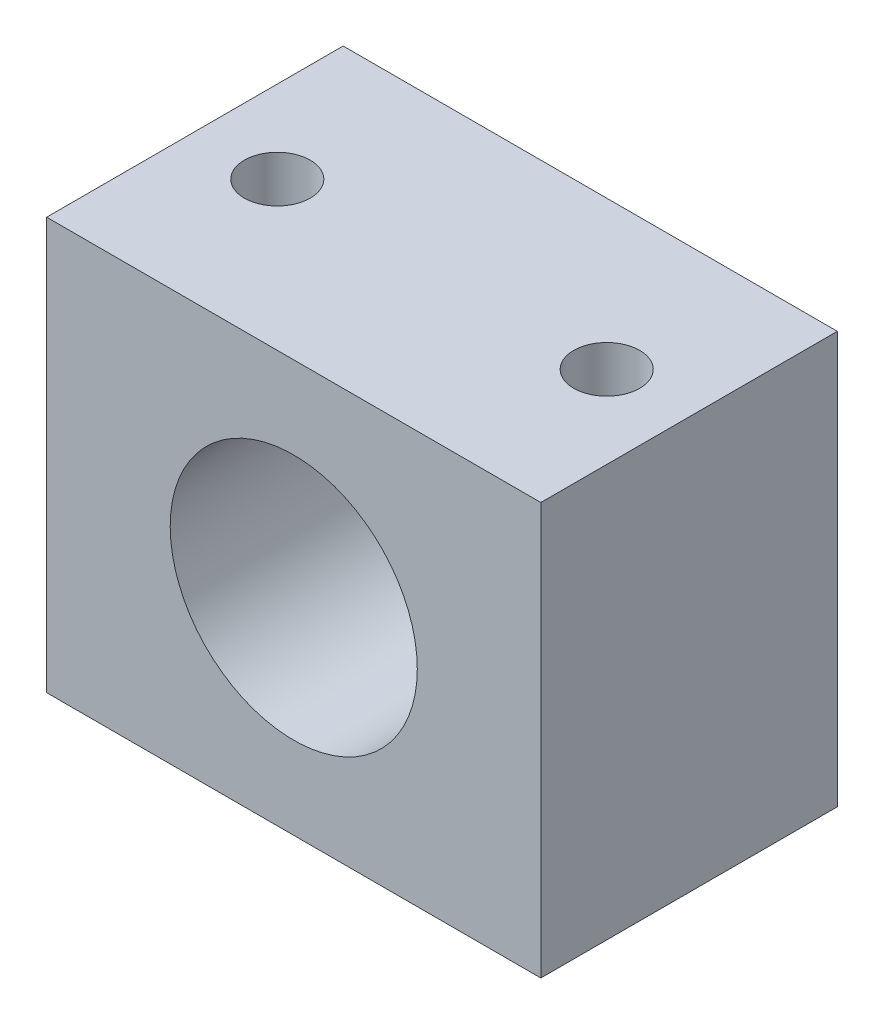
SolidWorks part; units mm, degrees
ref_plane "Front Plane" through (0, 0, 0) normal (0, 0, 1) x (1, 0, 0)
ref_plane "Top Plane" through (0, 0, 0) normal (0, 1, 0) x (1, 0, 0)
ref_plane "Right Plane" through (0, 0, 0) normal (1, 0, 0) x (0, 0, -1)
sketch "Sketch1" plane through (0, 0, 0) normal (0, 0, 1) x (1, 0, 0)
  line L1 (-15, 12.5) -> (15, 12.5)
  line L2 (-15, 12.5) -> (-15, -12.5)
  line L3 (-15, -12.5) -> (15, -12.5)
  line L4 (15, 12.5) -> (15, -12.5)
  line L5 (-15, 12.5) -> (15, -12.5) construction
  line L6 (-15, -12.5) -> (15, 12.5) construction
  circle A0 centre (0, 0) radius 7.5
  dimension "D1" = 15
  dimension "D2" = 25
  dimension "D3" = 30
extrude "Boss-Extrude1" add sketch "Sketch1" along normal blind 18
sketch "Sketch3" plane through (0, 12.5, 0) normal (0, 1, 0) x (1, 0, 0)
  line L0 (0, -1000) -> (0, 49000) construction
  line L1 (-1020, -9) -> (48980, -9) construction
  line L2 (-15, -18) -> (-15, 0) construction
  circle A0 centre (-10, -9) radius 2
  circle A1 centre (10, -9) radius 2
  point P8 (-15, -9)
  dimension "D2" = 4
  dimension "D1" = 5
extrude "Cut-Extrude1" cut sketch "Sketch3" against normal through all
